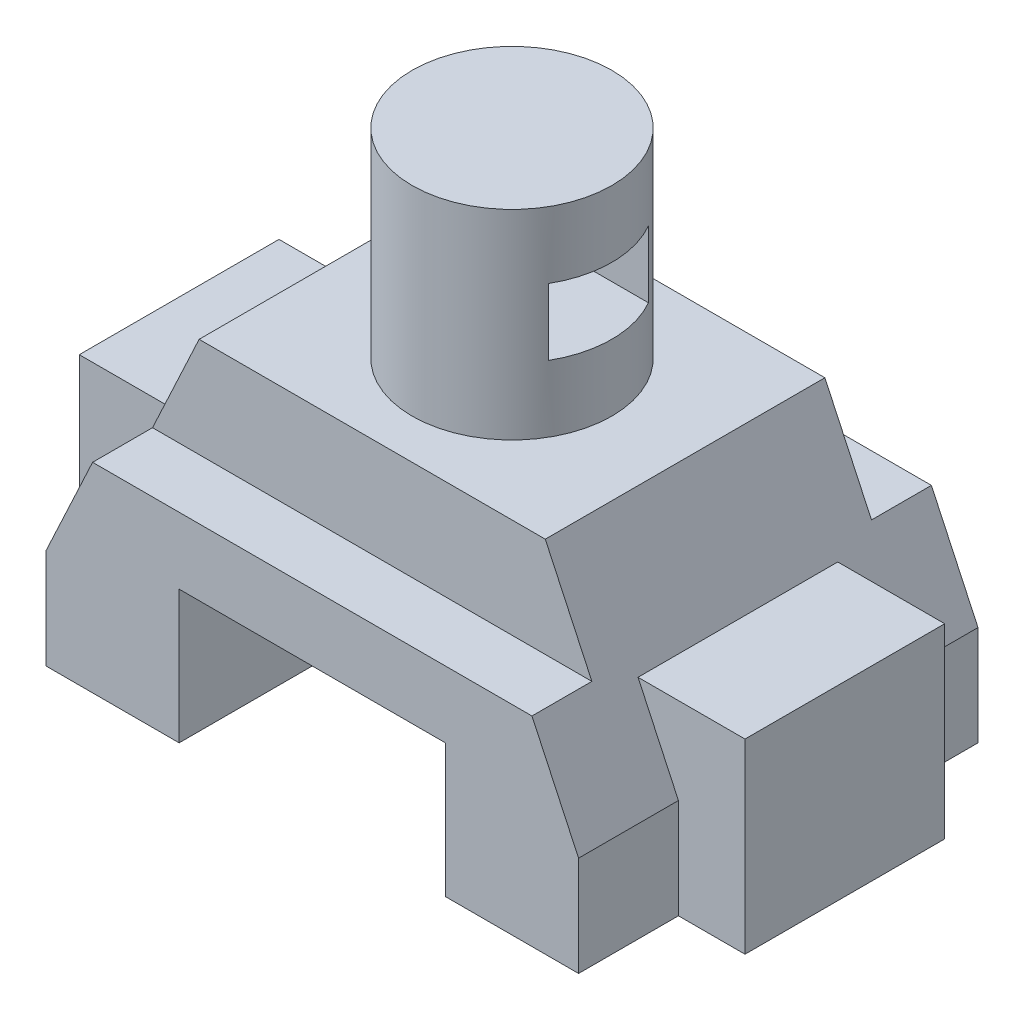
SolidWorks part; units mm, degrees
ref_plane "Front Plane" through (0, 0, 0) normal (0, 0, 1) x (1, 0, 0)
ref_plane "Top Plane" through (0, 0, 0) normal (0, 1, 0) x (1, 0, 0)
ref_plane "Right Plane" through (0, 0, 0) normal (1, 0, 0) x (0, 0, -1)
sketch "Sketch1" plane through (0, 0, 0) normal (0, 0, 1) x (1, 0, 0)
  line L0 (40, 0) -> (20, 0)
  line L1 (-40, 0) -> (-40, 15)
  line L2 (-40, 15) -> (-26, 45)
  line L3 (-26, 45) -> (26, 45)
  line L4 (26, 45) -> (40, 15)
  line L5 (40, 15) -> (40, 0)
  line L6 (-20, 0) -> (-20, 20)
  line L7 (-20, 20) -> (20, 20)
  line L8 (20, 20) -> (20, 0)
  line L9 (-20, 0) -> (-40, 0)
  point P13 (0, 0)
  dimension "D1" = 80
  dimension "D2" = 40
  dimension "D3" = 15
  dimension "D4" = 15
  dimension "D5" = 52
  dimension "D6" = 40
  dimension "D7" = 20
  dimension "D8" = 20
  dimension "D9" = 45
extrude "Boss-Extrude1" add sketch "Sketch1" along normal blind 60
ref_plane "Plane1" through (0, 45, 0) normal (0, 1, 0) x (1, 0, 0)
sketch "Sketch7" plane through (0, 45, 0) normal (0, 1, 0) x (1, 0, 0)
  line L0 (40, -60) -> (40, 0) construction
  line L1 (-40, 0) -> (40, 0)
  line L2 (-40, 0) -> (-40, -9)
  line L3 (-40, -9) -> (40, -9)
  line L4 (40, 0) -> (40, -9)
  line L6 (-40, -60) -> (40, -60)
  line L7 (-40, -60) -> (-40, -51)
  line L8 (-40, -51) -> (40, -51)
  line L9 (40, -60) -> (40, -51)
  dimension "D1" = 9
  dimension "D2" = 9
extrude "Cut-Extrude4" cut sketch "Sketch7" against normal blind 15
sketch "Sketch8" plane through (0, 45, 0) normal (0, 1, 0) x (1, 0, 0)
  line L0 (-26, -9) -> (26, -9) construction
  circle A0 centre (0, -30) radius 15
  dimension "D2" = 30
  dimension "D1" = 21
extrude "Boss-Extrude2" add sketch "Sketch8" along normal blind 30
ref_plane "Plane2" through (-40, 0, 0) normal (1, 0, 0) x (0, 0, -1)
sketch "Sketch10" plane through (-40, 0, 0) normal (1, 0, 0) x (0, 0, -1)
  line L0 (-60, 0) -> (0, 0) construction
  line L1 (-45, 0) -> (-15, 0)
  line L2 (-45, 0) -> (-45, 28)
  line L3 (-45, 28) -> (-15, 28)
  line L4 (-15, 0) -> (-15, 28)
  point P6 (-30, 0)
  dimension "D1" = 30
  dimension "D2" = 15
  dimension "D3" = 28
  dimension "D4" = 15
extrude "Boss-Extrude3" add sketch "Sketch10" along normal blind 90 and the other way blind 10
sketch "Sketch12" plane through (0, 0, 15) normal (0, 0, -1) x (-1, 0, 0)
  line L1 (-20, 0) -> (20, 0)
  line L2 (-20, 0) -> (-20, 20)
  line L3 (-20, 20) -> (20, 20)
  line L4 (20, 0) -> (20, 20)
extrude "Cut-Extrude5" cut sketch "Sketch12" against normal blind 90
ref_plane "Plane4" through (0, 0, 0) normal (1, 0, 0) x (0, 0, -1)
sketch "Sketch13" plane through (0, 0, 0) normal (1, 0, 0) x (0, 0, -1)
  line L0 (-45, 75) -> (-45, 45) construction
  line L1 (-37.5, 65) -> (-22.5, 65)
  line L2 (-37.5, 65) -> (-37.5, 55)
  line L3 (-37.5, 55) -> (-22.5, 55)
  line L4 (-22.5, 65) -> (-22.5, 55)
  line L5 (-51, 45) -> (-9, 45) construction
  dimension "D1" = 10
  dimension "D2" = 15
  dimension "D3" = 7.5
  dimension "D4" = 10
extrude "Cut-Extrude6" cut sketch "Sketch13" against normal through all and the other way through all
